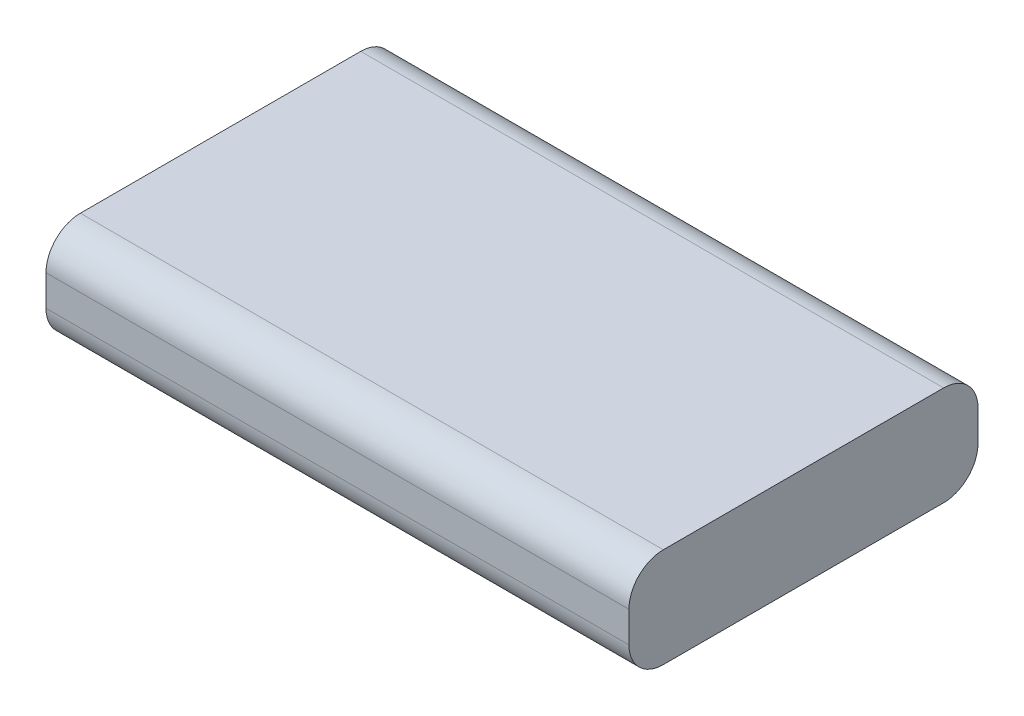
SolidWorks part; units mm, degrees
material "Battery"
ref_plane "Front Plane" through (0, 0, 0) normal (0, 0, 1) x (1, 0, 0)
ref_plane "Top Plane" through (0, 0, 0) normal (0, 1, 0) x (1, 0, 0)
ref_plane "Right Plane" through (0, 0, 0) normal (1, 0, 0) x (0, 0, -1)
sketch "Sketch1" plane through (0, 0, 0) normal (0, 1, 0) x (1, 0, 0)
  line L1 (0, 0) -> (84.84, 0)
  line L2 (0, 0) -> (0, 50.8)
  line L3 (0, 50.8) -> (84.84, 50.8)
  line L4 (84.84, 0) -> (84.84, 50.8)
  dimension "D1" = 84.84
  dimension "D2" = 50.8
extrude "Boss-Extrude1" add sketch "Sketch1" along normal blind 14.48
fillet "Fillet1" radius 5 4 edges at (42.42, 0, -50.8) (42.42, 14.48, -50.8) (42.42, 0, 0) (42.42, 14.48, 0)
